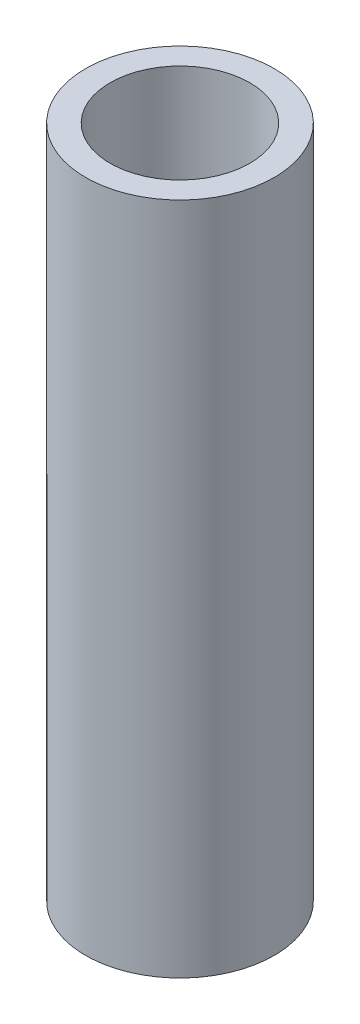
SolidWorks part; units mm, degrees
ref_plane "Front Plane" through (0, 0, 0) normal (0, 0, 1) x (1, 0, 0)
ref_plane "Top Plane" through (0, 0, 0) normal (0, 1, 0) x (1, 0, 0)
ref_plane "Right Plane" through (0, 0, 0) normal (1, 0, 0) x (0, 0, -1)
sketch "Sketch1" plane through (0, 0, 0) normal (0, 1, 0) x (1, 0, 0)
  circle A0 centre (0, 0) radius 7.8994
  circle A1 centre (0, 0) radius 10.668
  dimension "D1" = 21.336
  dimension "D2" = 15.7988
extrude "Boss-Extrude1" add sketch "Sketch1" along normal blind 76.2
